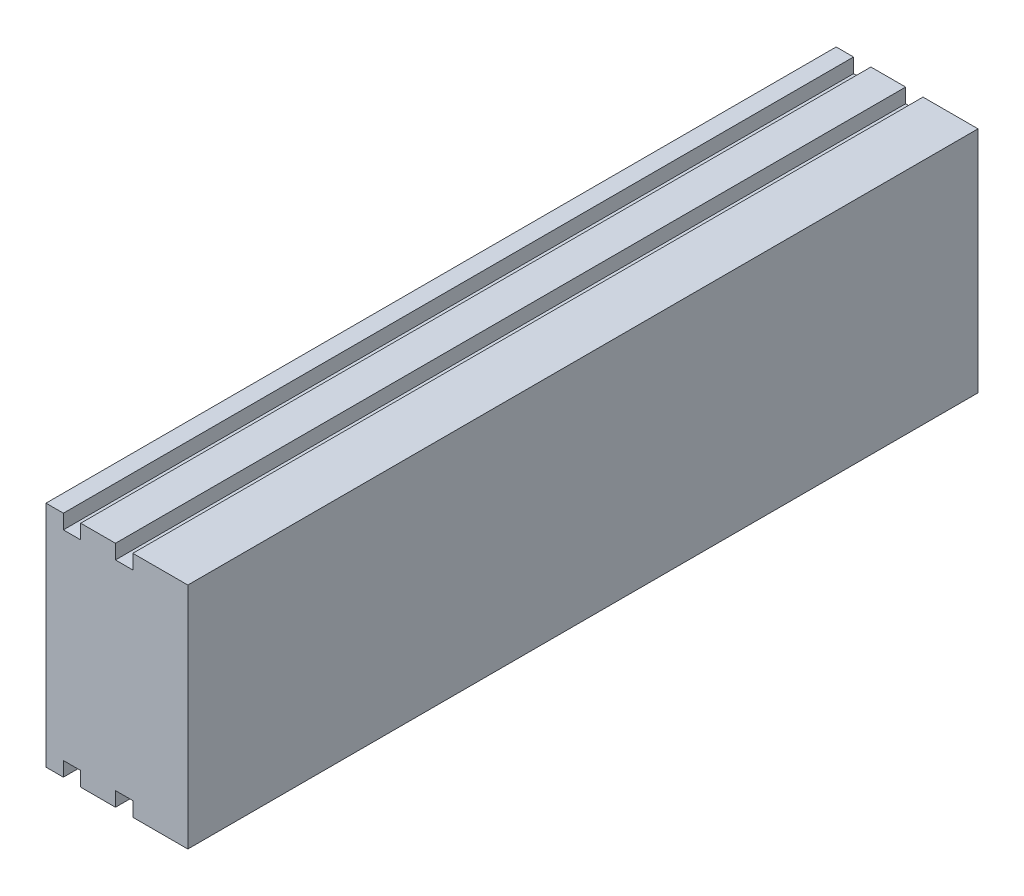
SolidWorks part; units mm, degrees
ref_plane "Plan de face" through (0, 0, 0) normal (0, 0, 1) x (1, 0, 0)
ref_plane "Plan de dessus" through (0, 0, 0) normal (0, 1, 0) x (1, 0, 0)
ref_plane "Plan de droite" through (0, 0, 0) normal (1, 0, 0) x (0, 0, -1)
sketch "Esquisse1" plane through (0, 0, 0) normal (0, 0, 1) x (1, 0, 0)
  line L1 (0, 0) -> (49, 0)
  line L2 (0, 0) -> (0, 79)
  line L3 (0, 79) -> (49, 79)
  line L4 (49, 0) -> (49, 79)
  dimension "D1" = 49
  dimension "D2" = 79
extrude "Boss.-Extru.1" add sketch "Esquisse1" along normal blind 273
sketch "Esquisse2" plane through (0, 0, 0) normal (0, -1, 0) x (1, 0, 0)
  line L0 (0, 273) -> (49, 273) construction
  line L1 (6, 273) -> (12, 273)
  line L2 (6, 273) -> (6, 0)
  line L3 (6, 0) -> (12, 0)
  line L4 (12, 273) -> (12, 0)
  line L5 (0, 0) -> (49, 0) construction
  line L7 (24, 273) -> (30, 273)
  line L8 (24, 273) -> (24, 0)
  line L9 (24, 0) -> (30, 0)
  line L10 (30, 273) -> (30, 0)
  dimension "D1" = 6
  dimension "D2" = 6
  dimension "D3" = 12
extrude "Enlèv. mat.-Extru.1" cut sketch "Esquisse2" against normal blind 5
ref_plane "Plan1" through (0, 39.5, 0) normal (0, -1, 0) x (-1, 0, 0)
mirror "Symétrie2" about plane through (0, 39.5, 0) normal (0, -1, 0) of "Enlèv. mat.-Extru.1"
